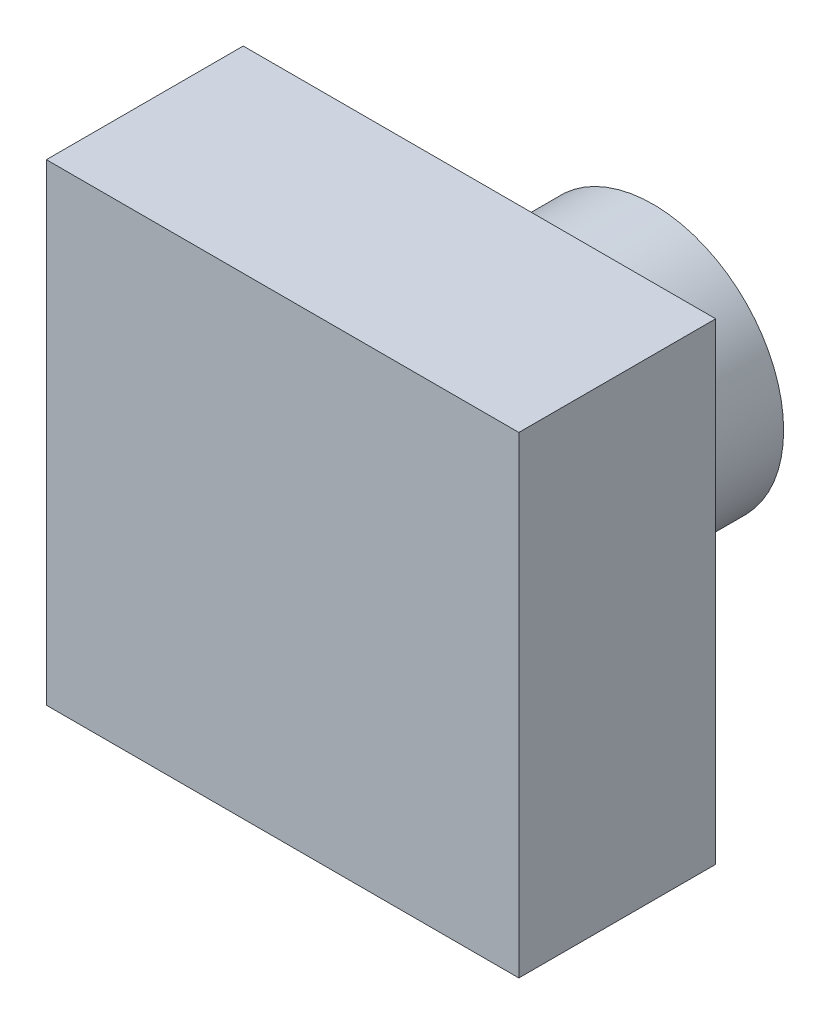
SolidWorks part; units mm, degrees
ref_plane "前视基准面" through (0, 0, 0) normal (0, 0, 1) x (1, 0, 0)
ref_plane "上视基准面" through (0, 0, 0) normal (0, 1, 0) x (1, 0, 0)
ref_plane "右视基准面" through (0, 0, 0) normal (1, 0, 0) x (0, 0, -1)
sketch "草图1" plane through (0, 0, 0) normal (0, 0, 1) x (1, 0, 0)
  circle A0 centre (0, 0) radius 3.315
  dimension "D1" = 6.63
extrude "凸台-拉伸1" add sketch "草图1" along normal blind 4.41
sketch "草图2" plane through (0, 0, 4.41) normal (0, 0, 1) x (1, 0, 0)
  line L1 (-6, 6) -> (6, 6)
  line L2 (-6, 6) -> (-6, -6)
  line L3 (-6, -6) -> (6, -6)
  line L4 (6, 6) -> (6, -6)
  circle A0 centre (0, 0) radius 3.315 construction
  dimension "D1" = 12
  dimension "D2" = 12
  dimension "D3" = 6
  dimension "D4" = 6
extrude "凸台-拉伸2" add sketch "草图2" along normal blind 5
